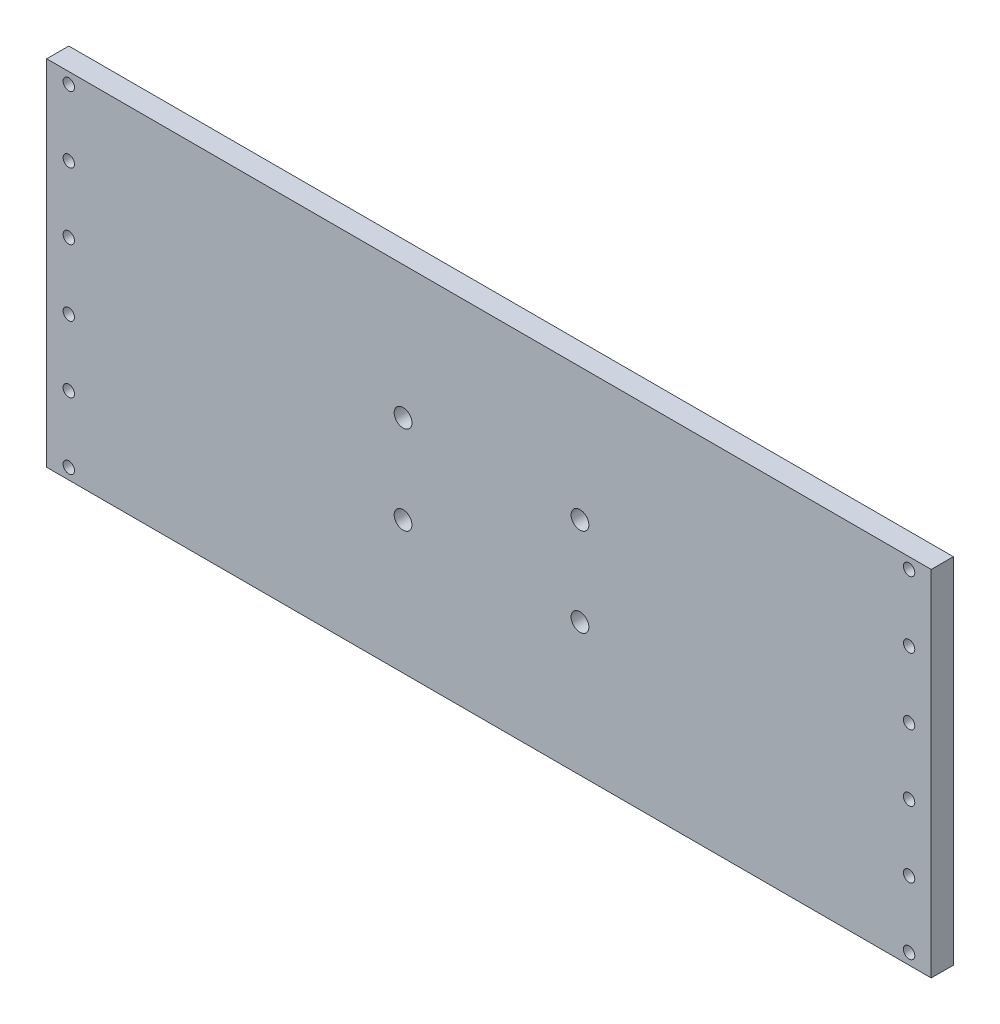
SolidWorks part; units mm, degrees
ref_plane "Front Plane" through (0, 0, 0) normal (0, 0, 1) x (1, 0, 0)
ref_plane "Top Plane" through (0, 0, 0) normal (0, 1, 0) x (1, 0, 0)
ref_plane "Right Plane" through (0, 0, 0) normal (1, 0, 0) x (0, 0, -1)
sketch "Sketch1" plane through (0, 0, 0) normal (0, 0, 1) x (1, 0, 0)
  line L1 (-127, 50.8) -> (127, 50.8)
  line L2 (-127, 50.8) -> (-127, -50.8)
  line L3 (-127, -50.8) -> (127, -50.8)
  line L4 (127, 50.8) -> (127, -50.8)
  line L5 (-127, 50.8) -> (127, -50.8) construction
  line L6 (-127, -50.8) -> (127, 50.8) construction
  point P0 (0, 0)
  dimension "D1" = 101.6
  dimension "D2" = 254
extrude "Boss-Extrude1" add sketch "Sketch1" along normal mid plane 6.35
hole_wizard "#4 Clearance Hole1" positions "Sketch7" profile "Sketch6" hole size "#4" standard "ANSI Inch" end condition through all
sketch "Sketch7" plane through (0, 0, 3.175) normal (0, 0, 1) x (1, 0, 0)
  line L0 (127, 50.8) -> (-127, 50.8) construction
  line L1 (-127, 50.8) -> (-127, -50.8) construction
  point P0 (-120.65, 47.625)
  point P11 (-120.65, 28.575)
  point P12 (-120.65, 9.525)
  point P13 (-120.65, -9.525)
  point P14 (-120.65, -28.575)
  point P15 (-120.65, -47.625)
  dimension "D1" = 3.175
  dimension "D2" = 6.35
  dimension "D3" = 6
sketch "Sketch6" plane through (-120.65, 47.625, 3.175) normal (1, 0, 0) x (0, -1, 0)
  line L0 (0, 0) -> (0, 6.35)
  line L1 (0, 6.35) -> (1.6319, 6.35)
  line L2 (1.6319, 6.35) -> (1.6319, 0)
  line L5 (1.6319, 0) -> (0, 0)
  line L11 (0, -6.35) -> (0, 107.95) construction
  dimension "Thru Hole Dia." = 3.2639
  dimension "Thru Hole Depth" = 6.35
mirror "Mirror1" about plane through (0, 0, 0) normal (1, 0, 0) of "#4 Clearance Hole1"
hole_wizard "#10 Clearance Hole1" positions "Sketch9" profile "Sketch8" hole size "#10" standard "ANSI Inch" end condition through all
sketch "Sketch9" plane through (0, 0, 3.175) normal (0, 0, 1) x (1, 0, 0)
  line L0 (-24.6595, 12.7) -> (-24.6595, -12.7) construction
  point P0 (-24.6595, 12.7)
  point P8 (26.1405, 12.7)
  point P9 (26.1405, -12.7)
  point P10 (-24.6595, -12.7)
  point P15 (-24.6595, 0)
  dimension "D1" = 2
sketch "Sketch8" plane through (-24.6595, 12.7, 3.175) normal (1, 0, 0) x (0, -1, 0)
  line L0 (0, 0) -> (0, 6.35)
  line L1 (0, 6.35) -> (2.5527, 6.35)
  line L2 (2.5527, 6.35) -> (2.5527, 0)
  line L5 (2.5527, 0) -> (0, 0)
  line L11 (0, -6.35) -> (0, 107.95) construction
  dimension "Thru Hole Dia." = 5.1054
  dimension "Thru Hole Depth" = 6.35
